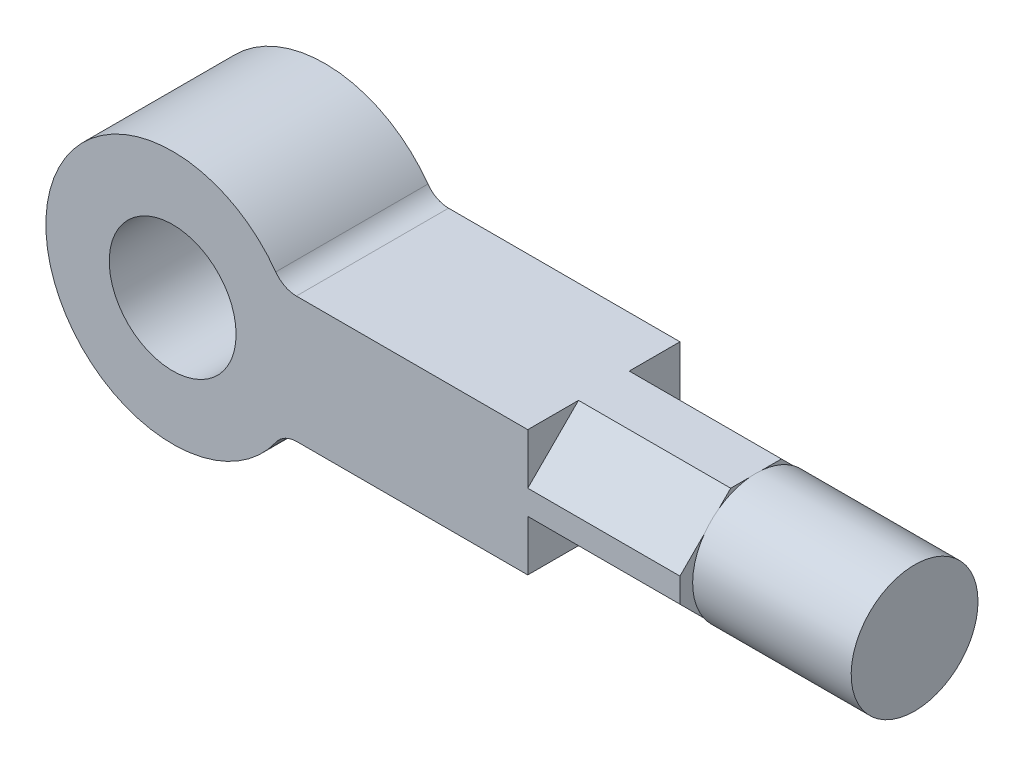
SolidWorks part; units mm, degrees
ref_plane "Front Plane" through (0, 0, 0) normal (0, 0, 1) x (1, 0, 0)
ref_plane "Top Plane" through (0, 0, 0) normal (0, 1, 0) x (1, 0, 0)
ref_plane "Right Plane" through (0, 0, 0) normal (1, 0, 0) x (0, 0, -1)
sketch "Sketch1" plane through (0, 0, 0) normal (0, 0, 1) x (1, 0, 0)
  line L1 (19.5062, 9.9824) -> (80, 9.9824)
  line L3 (19.5912, -9.863) -> (80, -9.863)
  line L4 (80, 9.9824) -> (80, -9.863)
  circle A0 centre (0, 0) radius 10
  arc A1 (16.2552, 11.652) -> (16.326, -11.5525) centre (0, 0) ccw
  arc A2 (19.5912, -9.863) -> (16.326, -11.5525) centre (19.5912, -13.863) ccw
  arc A3 (19.5062, 9.9824) -> (16.2552, 11.652) centre (19.5062, 13.9824) cw
  dimension "D1" = 4
extrude "Boss-Extrude4" add sketch "Sketch1" along normal blind 24
sketch "Sketch7" plane through (80, 0, 0) normal (1, 0, 0) x (0, 0, -1)
  line L0 (-8, 9.9824) -> (0, 9.9824)
  line L1 (-24, 9.9824) -> (0, 9.9824) construction
  line L2 (0, 9.9824) -> (0, 1.9824)
  line L3 (0, -9.863) -> (0, 9.9824) construction
  line L4 (0, 1.9824) -> (-8, 9.9824)
  line L5 (-24, 9.9824) -> (-16, 9.9824)
  line L7 (-16, 9.9824) -> (-24, 1.9824)
  line L9 (-24, -9.863) -> (-24, 9.9824) construction
  line L10 (-24, 1.9824) -> (-24, 9.9824)
  line L11 (-24, -9.863) -> (-24, -1.863)
  line L12 (-24, -1.863) -> (-16, -9.863)
  line L13 (-24, -9.863) -> (0, -9.863) construction
  line L14 (-16, -9.863) -> (-24, -9.863)
  line L15 (0, -9.863) -> (0, -1.863)
  line L16 (0, -1.863) -> (-8, -9.863)
  line L17 (-24, -9.863) -> (0, -9.863) construction
  line L18 (-8, -9.863) -> (0, -9.863)
  point P16 (-12, 0.0597)
extrude "Cut-Extrude1" cut sketch "Sketch7" against normal blind 24
sketch "Sketch8" plane through (80, 0, 0) normal (1, 0, 0) x (0, 0, -1)
  circle A0 centre (-12, 0.0299) radius 10
  point P11 (-12, 0.0299)
extrude "Boss-Extrude5" add sketch "Sketch8" along normal blind 25
